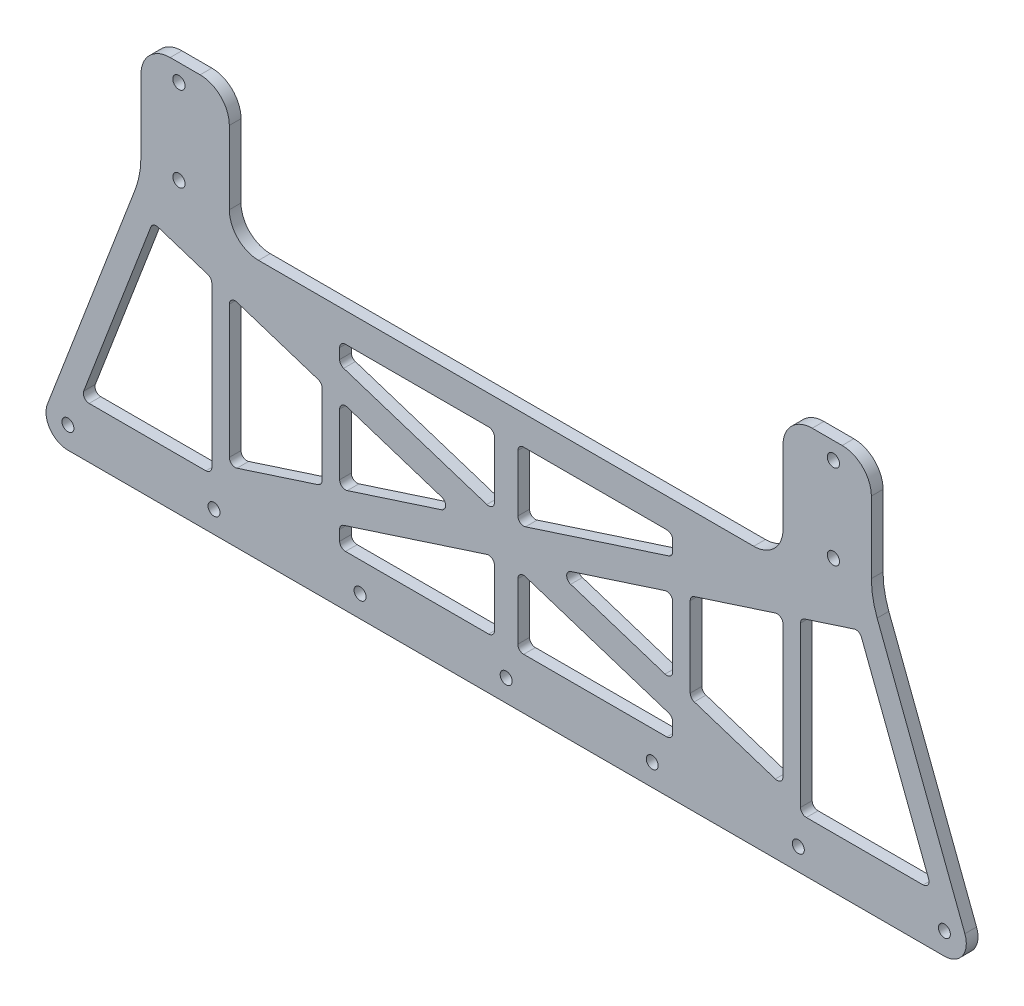
SolidWorks part; units mm, degrees
material "Thornel Mat VMA"
ref_plane "前视基准面" through (0, 0, 0) normal (0, 0, 1) x (1, 0, 0)
ref_plane "上视基准面" through (0, 0, 0) normal (0, 1, 0) x (1, 0, 0)
ref_plane "右视基准面" through (0, 0, 0) normal (1, 0, 0) x (0, 0, -1)
sketch "草图1" plane through (0, 0, 0) normal (0, 0, 1) x (1, 0, 0)
  line L1 (-125, -70) -> (125, -70)
  line L2 (-125, -70) -> (-125, 70)
  line L3 (-125, 70) -> (125, 70)
  line L4 (125, -70) -> (125, 70)
  line L5 (-125, -70) -> (125, 70) construction
  line L6 (-125, 70) -> (125, -70) construction
  point P0 (0, 0)
  dimension "D1" = 250
  dimension "D2" = 140
extrude "凸台-拉伸1" add sketch "草图1" along normal blind 4
sketch "草图2" plane through (0, 0, 4) normal (0, 0, 1) x (1, 0, 0)
  line L0 (0, 0) -> (0, 51.6) construction
  line L1 (125, 70) -> (-125, 70) construction
  line L2 (-108.75, 38.2) -> (108.75, 38.2) construction
  line L3 (-108.75, 38.2) -> (-108.75, 65) construction
  line L4 (-108.75, 65) -> (108.75, 65) construction
  line L5 (108.75, 38.2) -> (108.75, 65) construction
  line L6 (-108.75, 38.2) -> (108.75, 65) construction
  line L7 (-108.75, 65) -> (108.75, 38.2) construction
  circle A0 centre (-108.75, 65) radius 1.55
  circle A1 centre (-108.75, 38.2) radius 1.55
  circle A2 centre (108.75, 65) radius 1.55
  circle A3 centre (108.75, 38.2) radius 1.55
  dimension "D4" = 3.1
  dimension "D1" = 26.8
  dimension "D2" = 217.5
  dimension "D3" = 5
extrude "切除-拉伸1" cut sketch "草图2" against normal blind 4
sketch "草图4" plane through (0, 0, 4) normal (0, 0, 1) x (1, 0, 0)
  line L0 (-125, -70) -> (125, -70) construction
  line L1 (-175, -40) -> (175, -40)
  line L2 (-175, -40) -> (-175, -70)
  line L3 (-175, -70) -> (175, -70)
  line L4 (175, -40) -> (175, -70)
  line L5 (-175, -40) -> (175, -70) construction
  line L6 (-175, -70) -> (175, -40) construction
  line L7 (0, 0) -> (0, -55) construction
  line L8 (125, -70) -> (125, 70) construction
  point P0 (0, -55)
  dimension "D1" = 50
  dimension "D2" = 30
extrude "凸台-拉伸2" add sketch "草图4" against normal up to surface (4 mm away) up to face at (-107.2, 38.2, 0)
sketch "草图5" plane through (0, 0, 4) normal (0, 0, 1) x (1, 0, 0)
  line L0 (-125, 70) -> (-175, -40)
  line L1 (125, 70) -> (175, -40)
  line L2 (175, -40) -> (-175, -40)
  line L3 (-125, 70) -> (125, 70)
  circle A0 centre (108.75, 38.2) radius 1.55 construction
  circle A1 centre (108.75, 65) radius 1.55 construction
  circle A2 centre (-108.75, 38.2) radius 1.55 construction
  circle A3 centre (-108.75, 65) radius 1.55 construction
  circle A4 centre (108.75, 38.2) radius 1.55
  circle A5 centre (108.75, 65) radius 1.55
  circle A6 centre (-108.75, 38.2) radius 1.55
  circle A7 centre (-108.75, 65) radius 1.55
  line M9 (-125, 70) -> (-125, -40)
  line M10 (-125, -40) -> (-175, -40)
  line M14 (175, -40) -> (125, -40)
  line M15 (125, -40) -> (125, 70)
extrude "凸台-拉伸3" add sketch "草图5" against normal up to surface (4 mm away) contours L0 M9 M10 | L1 M15 M14 up to face at (0, -20, 0)
sketch "草图3" plane through (0, 0, 4) normal (0, 0, 1) x (1, 0, 0)
  line L0 (0, 0) -> (0, -56.4) construction
  line L1 (0, -56.4) -> (50, -56.4) construction
  line L2 (0, -56.4) -> (-50, -56.4) construction
  circle A0 centre (50, -56.4) radius 2.05
  circle A1 centre (0, -56.4) radius 2.05
  circle A2 centre (100, -56.4) radius 2.05
  circle A3 centre (150, -56.4) radius 2.05
  circle A4 centre (-50, -56.4) radius 2.05
  circle A5 centre (-100, -56.4) radius 2.05
  circle A6 centre (-150, -56.4) radius 2.05
  dimension "D2" = 4.1
  dimension "D1" = 56.4
  dimension "D4" = 50
  dimension "D6" = 50
  dimension "D3" = 4
  dimension "D5" = 4
extrude "切除-拉伸2" cut sketch "草图3" against normal blind 4
sketch "草图6" plane through (0, 0, 4) normal (0, 0, 1) x (1, 0, 0)
  line L0 (-94.75, 70) -> (-94.75, 25)
  line L1 (125, 70) -> (-125, 70) construction
  line L2 (-94.75, 25) -> (94.75, 25)
  line L3 (94.75, 25) -> (94.75, 70)
  line L4 (94.75, 70) -> (-94.75, 70)
  line L5 (0, 0) -> (0, 70) construction
  circle A0 centre (-108.75, 65) radius 1.55 construction
  dimension "D1" = 14
  dimension "D2" = 45
extrude "切除-拉伸3" cut sketch "草图6" against normal blind 4
sketch "草图7" plane through (0, 0, 4) normal (0, 0, 1) x (1, 0, 0)
  line L0 (-125, 70) -> (-125, 30)
  line L1 (-175, -40) -> (-125, 70)
  line L2 (0, 0) -> (0, 25) construction
  line L3 (-94.75, 25) -> (94.75, 25) construction
  line L4 (175, -40) -> (125, 70)
  line L5 (125, 70) -> (125, 30)
  line L6 (-125, 30) -> (-175, -40)
  line L7 (125, 30) -> (175, -40)
  dimension "D1" = 40
extrude "切除-拉伸4" cut sketch "草图7" against normal blind 4
sketch "草图8" plane through (0, 0, 4) normal (0, 0, 1) x (1, 0, 0)
  line L1 (-150, -63.9) -> (150, -63.9)
  line L2 (0, 0) -> (0, 67.7549) construction
  line L3 (125, 30) -> (228.1556, 30)
  line L4 (228.1556, 30) -> (175, -70)
  line L5 (175, -70) -> (-175, -70)
  line L6 (-175, -70) -> (-228.1556, 30)
  line L7 (-228.1556, 30) -> (-125, 30)
  line L8 (-125, 30) -> (-157.0055, -53.7219)
  line L9 (125, 30) -> (157.0055, -53.7219)
  arc A0 (-157.0055, -53.7219) -> (-150, -63.9) centre (-150, -56.4) ccw
  arc A2 (150, -63.9) -> (157.0055, -53.7219) centre (150, -56.4) ccw
  dimension "D1" = 456.3112
  dimension "D2" = 15
extrude "切除-拉伸5" cut sketch "草图8" against normal blind 4
fillet "圆角1" radius 10 2 edges at (94.75, 25, 2) (-94.75, 25, 2)
sketch "草图9" plane through (0, 0, 4) normal (0, 0, 1) x (1, 0, 0)
  line L0 (0, 0) -> (0, -15.7) construction
  line L1 (-94.75, -46.4) -> (94.75, -46.4)
  line L2 (-94.75, -46.4) -> (-94.75, 15)
  line L3 (-94.75, 15) -> (94.75, 15)
  line L4 (94.75, -46.4) -> (94.75, 15)
  line L5 (-94.75, -46.4) -> (94.75, 15) construction
  line L6 (-94.75, 15) -> (94.75, -46.4) construction
  line L7 (-84.75, 25) -> (84.75, 25) construction
  line L8 (-94.75, 70) -> (-94.75, 35) construction
  line L9 (0, 15) -> (0, -46.4) construction
  line L10 (-4, 15) -> (-4, -46.4)
  line L11 (4, 15) -> (4, -46.4)
  line L12 (-60, 15) -> (-60, -46.4) construction
  line L13 (60, 15) -> (60, -46.4) construction
  line L14 (-96.2912, 10.2434) -> (93.2088, -51.1566)
  line L15 (-93.2088, -51.1566) -> (96.2912, 10.2434)
  line L16 (-93.2088, 19.7566) -> (96.2912, -41.6434)
  line L17 (-96.2912, -41.6434) -> (93.2088, 19.7566)
  line L18 (-63, 15) -> (-63, -46.4)
  line L19 (57, 15) -> (57, -46.4)
  line L20 (-57, 15) -> (-57, -46.4)
  line L21 (63, 15) -> (63, -46.4)
  circle A0 centre (0, -56.4) radius 2.05 construction
  point P0 (0, -15.7)
  dimension "D1" = 10
  dimension "D2" = 10
  dimension "D5" = 60
  dimension "D6" = 60
  dimension "D3" = 4
  dimension "D4" = 4
  dimension "D7" = 5
  dimension "D8" = 5
  dimension "D9" = 3
  dimension "D10" = 3
extrude "切除-拉伸6" cut sketch "草图9" against normal blind 4 contours L15 L20 L1 L10 | L14 L20 L17 | L3 L20 L16 L10 | L19 L3 L11 L17 | L19 L15 L16 | L19 L14 L11 L1 | L15 L21 L16 L4 | L18 L14 L2 L17
sketch "草图10" plane through (0, 0, 4) normal (0, 0, 1) x (1, 0, 0)
  line L0 (-100.75, 28.2) -> (-100.75, -46.4)
  line L1 (-100.75, -46.4) -> (-145.6419, -46.4)
  line L2 (-117.1235, 28.2) -> (-100.75, 28.2)
  line L3 (-94.75, -41.1441) -> (-94.75, 9.7441) construction
  line L4 (-57, -46.4) -> (-4, -46.4) construction
  line L5 (0, 0) -> (0, -63.9) construction
  line L6 (150, -63.9) -> (-150, -63.9) construction
  line L7 (117.1235, 28.2) -> (100.75, 28.2)
  line L8 (100.75, -46.4) -> (145.6419, -46.4)
  line L9 (100.75, 28.2) -> (100.75, -46.4)
  line L10 (-117.1235, 28.2) -> (-145.6419, -46.4)
  line L11 (-157.0055, -53.7219) -> (-125, 30) construction
  line L12 (117.1235, 28.2) -> (145.6419, -46.4)
  circle A2 centre (-108.75, 38.2) radius 1.55 construction
  dimension "D2" = 6
  dimension "D1" = 8
  dimension "D3" = 10
extrude "切除-拉伸7" cut sketch "草图10" against normal blind 4
fillet "圆角2" radius 2 38 edges at (-4, -9.148, 2) (-57, 8.0245, 2) (-57, 15, 2) (-4, 15, 2) (-57, -28.9127, 2) (-57, -2.4873, 2) (-16.2214, -15.7, 2) (16.2214, -15.7, 2) (57, -2.4873, 2) (57, -28.9127, 2) (4, -9.148, 2) (4, 15, 2) (57, 15, 2) (57, 8.0245, 2) (4, -46.4, 2) (4, -22.252, 2) (57, -39.4245, 2) (57, -46.4, 2) (94.75, -41.1441, 2) (63, -30.8568, 2) (63, -0.5432, 2) (94.75, 9.7441, 2) (-94.75, 9.7441, 2) (-63, -0.5432, 2) (-63, -30.8568, 2) (-4, -46.4, 2) (-57, -46.4, 2) (-57, -39.4245, 2) (-4, -22.252, 2) (100.75, -46.4, 2) (100.75, 28.2, 2) (-145.6419, -46.4, 2) (-117.1235, 28.2, 2) (-100.75, 28.2, 2) (-94.75, -41.1441, 2) (-100.75, -46.4, 2) (145.6419, -46.4, 2) (117.1235, 28.2, 2)
fillet "圆角3" radius 10 4 edges at (125, 70, 2) (94.75, 70, 2) (-94.75, 70, 2) (-125, 70, 2)
fillet "圆角4" radius 30 2 edges at (125, 30, 2) (-125, 30, 2)
sketch "草图11" plane through (0, 0, 4) normal (0, 0, 1) x (1, 0, 0)
  circle A0 centre (108.75, 38.2) radius 1.55 construction
  circle A1 centre (108.75, 65) radius 1.55 construction
  circle A2 centre (-108.75, 38.2) radius 1.55 construction
  circle A3 centre (-108.75, 65) radius 1.55 construction
  circle A4 centre (108.75, 38.2) radius 1.55
  circle A5 centre (108.75, 65) radius 1.55
  circle A6 centre (-108.75, 38.2) radius 1.55
  circle A7 centre (-108.75, 65) radius 1.55
extrude "凸台-拉伸4" add sketch "草图11" against normal up to surface (4 mm away) up to face at (-115.9734, -8.9465, 0)
sketch "草图14" plane through (0, 0, 4) normal (0, 0, 1) x (1, 0, 0)
  line L0 (100.75, 11.6882) -> (120.9354, 18.2285)
  line L1 (100.75, 26.2) -> (100.75, -44.4) construction
  line L2 (144.6043, -43.6858) -> (117.615, 26.9142) construction
  line L3 (64.3835, -0.095) -> (92.1335, 8.8963) construction
  line L4 (115.7469, 28.2) -> (102.75, 28.2) construction
  line L5 (120.9354, 18.2285) -> (117.615, 26.9142)
  line L6 (115.7469, 28.2) -> (102.75, 28.2)
  line L7 (100.75, 26.2) -> (100.75, 11.6882)
  line L8 (0, -77.4534) -> (0, 43.6963) construction
  line L9 (-100.75, 26.2) -> (-100.75, 11.6882)
  line L10 (-115.7469, 28.2) -> (-102.75, 28.2)
  line L11 (-120.9354, 18.2285) -> (-117.615, 26.9142)
  line L12 (-100.75, 11.6882) -> (-120.9354, 18.2285)
  arc A0 (117.615, 26.9142) -> (115.7469, 28.2) centre (115.7469, 26.2) ccw construction
  arc A1 (102.75, 28.2) -> (100.75, 26.2) centre (102.75, 26.2) ccw construction
  arc A2 (117.615, 26.9142) -> (115.7469, 28.2) centre (115.7469, 26.2) ccw
  arc A3 (102.75, 28.2) -> (100.75, 26.2) centre (102.75, 26.2) ccw
  arc A4 (-102.75, 28.2) -> (-100.75, 26.2) centre (-102.75, 26.2) cw
  arc A5 (-117.615, 26.9142) -> (-115.7469, 28.2) centre (-115.7469, 26.2) cw
extrude "凸台-拉伸5" add sketch "草图14" against normal up to surface (4 mm away) up to face at (-115.9734, -8.9465, 0)
sketch "草图13" plane through (0, 0, 4) normal (0, 0, 1) x (1, 0, 0)
  line L0 (0, -82.0396) -> (0, 76.3079) construction
  circle A0 centre (112, 35.1) radius 2.1
  circle A1 centre (112, 64.1) radius 2.1
  circle A2 centre (-112, 64.1) radius 2.1
  circle A3 centre (-112, 35.1) radius 2.1
  dimension "D1" = 4.2
extrude "切除-拉伸12" cut sketch "草图13" against normal up to surface (4 mm away) up to face at (-118.8042, -25.3124, 0)
fillet "圆角5" radius 2 4 edges at (-100.75, 11.6882, 2) (-120.9354, 18.2285, 2) (100.75, 11.6882, 2) (120.9354, 18.2285, 2)
